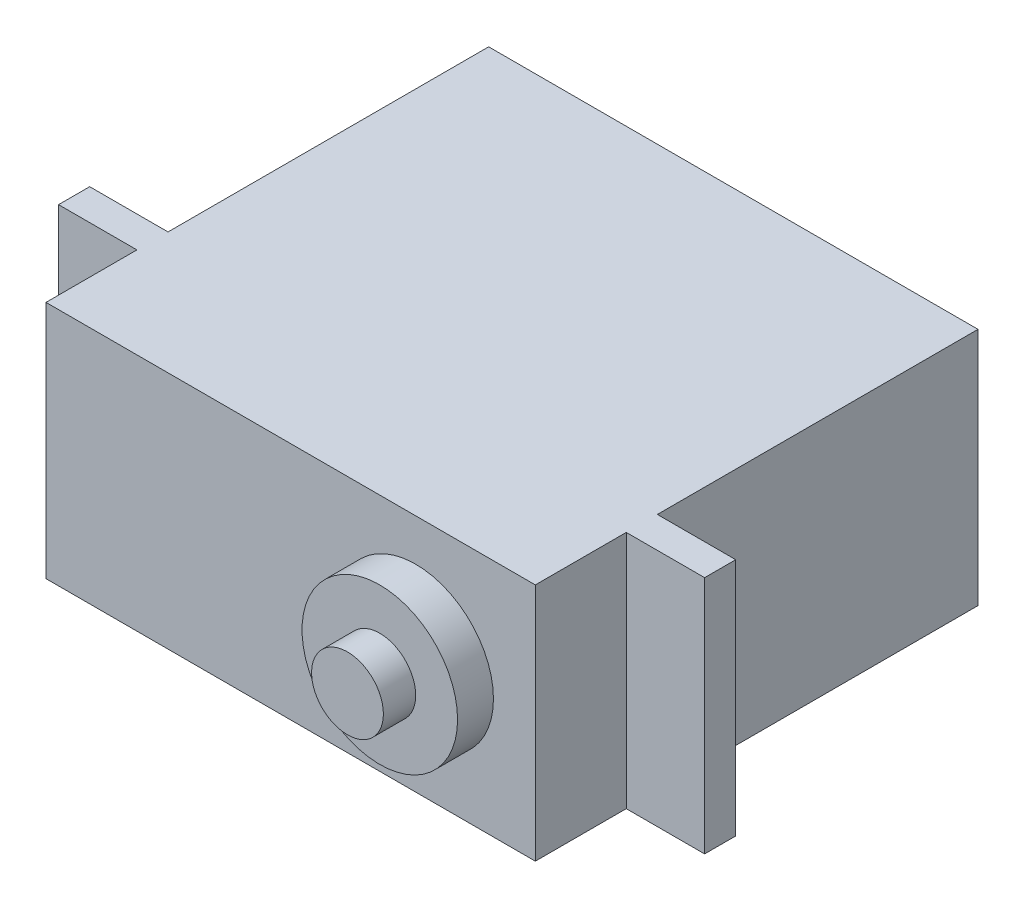
SolidWorks part; units mm, degrees
ref_plane "Front Plane" through (0, 0, 0) normal (0, 0, 1) x (1, 0, 0)
ref_plane "Top Plane" through (0, 0, 0) normal (0, 1, 0) x (1, 0, 0)
ref_plane "Right Plane" through (0, 0, 0) normal (1, 0, 0) x (0, 0, -1)
sketch "Case_40p9_x_20_x_37_Profile" plane through (0, 0, 0) normal (0, 0, 1) x (1, 0, 0)
  line L1 (-18.4, -10) -> (22.5, -10)
  line L2 (-18.4, -10) -> (-18.4, 10)
  line L3 (-18.4, 10) -> (22.5, 10)
  line L4 (22.5, -10) -> (22.5, 10)
extrude "Case_40p9_x_20_x_37" add sketch "Case_40p9_x_20_x_37_Profile" along normal blind 37 from offset 28.5
sketch "Mounting_tabs_54_x_20_x_2p6_Profile" plane through (0, 0, 0) normal (0, 0, 1) x (1, 0, 0)
  line L1 (-24.95, -10) -> (29.05, -10)
  line L2 (-24.95, -10) -> (-24.95, 10)
  line L3 (-24.95, 10) -> (29.05, 10)
  line L4 (29.05, -10) -> (29.05, 10)
extrude "Mounting_tabs_54_x_20_x_2p6" add sketch "Mounting_tabs_54_x_20_x_2p6_Profile" along normal blind 2.6 from offset 1.7
sketch "Output_boss_D13_Profile" plane through (0, 0, 0) normal (0, 0, 1) x (1, 0, 0)
  circle A0 centre (12.5, 0) radius 6.5
extrude "Output_boss_D13" add sketch "Output_boss_D13_Profile" along normal blind 3 from offset 8.5
sketch "Output_shaft_envelope_D6_Profile" plane through (0, 0, 0) normal (0, 0, 1) x (1, 0, 0)
  circle A0 centre (12.5, 0) radius 3
extrude "Output_shaft_envelope_D6" add sketch "Output_shaft_envelope_D6_Profile" along normal blind 5.7 from offset 8.5
